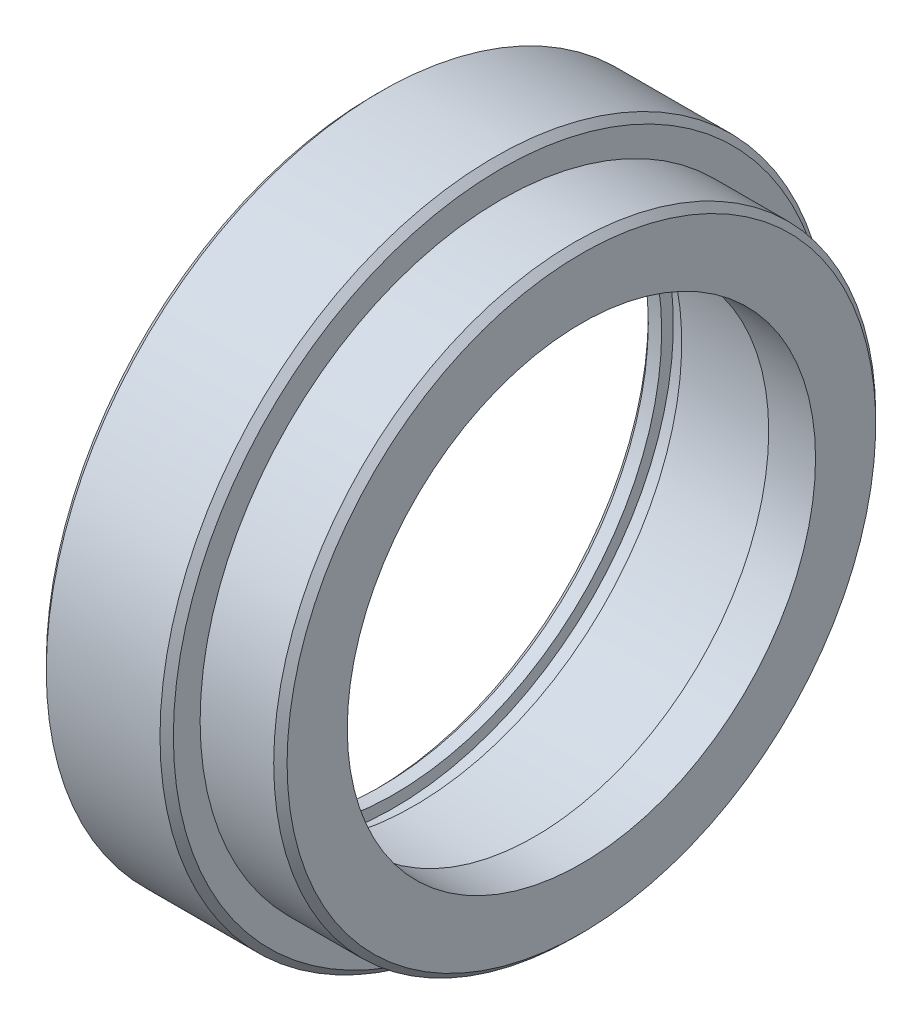
SolidWorks part; units mm, degrees
material "AISI 304"
ref_plane "Спереди" through (0, 0, 0) normal (0, 0, 1) x (1, 0, 0)
ref_plane "Сверху" through (0, 0, 0) normal (0, 1, 0) x (1, 0, 0)
ref_plane "Справа" through (0, 0, 0) normal (1, 0, 0) x (0, 0, -1)
sketch "Эскиз1" plane through (0, 0, 0) normal (0, 0, 1) x (1, 0, 0)
  line L0 (0, 0) -> (74.1, 0) construction
  line L1 (31, 35) -> (31, 45)
  line L3 (19, 45) -> (19, 50)
  line L4 (19, 50) -> (0, 50)
  line L6 (0, 40) -> (24, 40)
  line L9 (19, 45) -> (31, 45)
  line L11 (0, 40) -> (0, 50)
  line L15 (31, 35) -> (24, 35)
  line L16 (24, 35) -> (24, 40)
  dimension "D1" = 80
  dimension "D2" = 70
  dimension "D3" = 12
  dimension "D4" = 100
  dimension "D5" = 90
  dimension "D6" = 7
  dimension "D8" = 19
revolve "Повернуть1" add sketch "Эскиз1" angle 360 about L0
chamfer "Фаска1" distance 1 angle 45 4 edges at (19, 0, 50) (31, 0, 45) (0, 0, 40) (0, 0, 50)
sketch "Эскиз2" plane through (0, 0, 0) normal (0, 0, 1) x (1, 0, 0)
  line L0 (0, 0) -> (31, 0) construction
  line L1 (31, -35) -> (31, 35) construction
  line L3 (6, 41.75) -> (3, 41.75)
  line L4 (6, 41.75) -> (6, 0)
  line L5 (6, 0) -> (3, 0)
  line L6 (3, 41.75) -> (3, 0)
  dimension "D1" = 6
  dimension "D2" = 83.5
  dimension "D3" = 3
revolve "Вырез-Повернуть1" cut sketch "Эскиз2" angle 360 about L0
